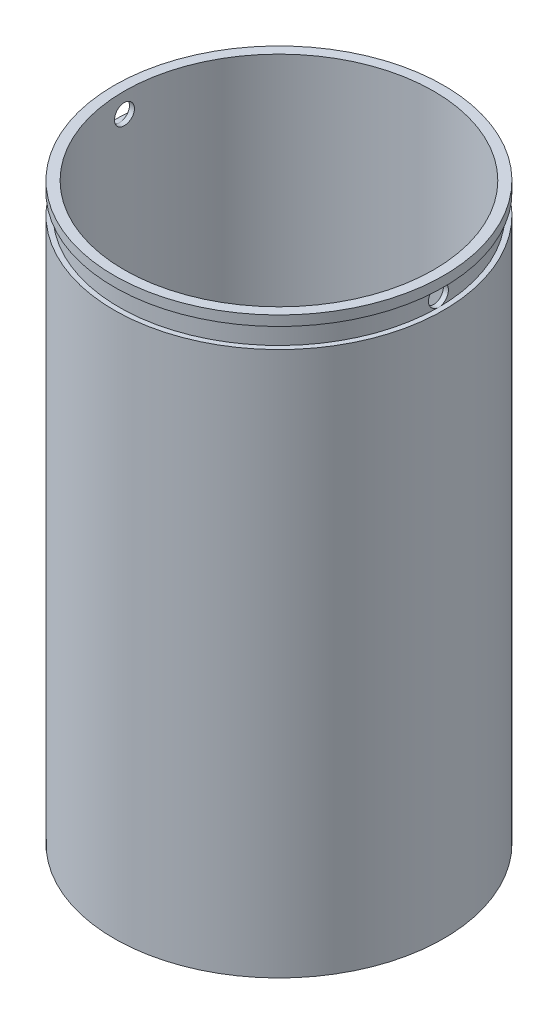
SolidWorks part; units mm, degrees
ref_plane "Plan de face" through (0, 0, 0) normal (0, 0, 1) x (1, 0, 0)
ref_plane "Plan de dessus" through (0, 0, 0) normal (0, 1, 0) x (1, 0, 0)
ref_plane "Plan de droite" through (0, 0, 0) normal (1, 0, 0) x (0, 0, -1)
sketch "Esquisse1" plane through (0, 0, 0) normal (0, 0, 1) x (1, 0, 0)
  line L0 (0, 0) -> (0, 109)
  line L1 (0, 109) -> (1, 109)
  line L2 (1, 109) -> (1, 113)
  line L3 (1, 113) -> (0, 113)
  line L4 (0, 113) -> (0, 115)
  line L5 (0, 115) -> (33, 115)
  line L6 (33, 115) -> (33, 0)
  line L7 (33, 0) -> (0, 0)
  line L8 (33, 183.3357) -> (33, -81.131) construction
  dimension "D1" = 109
  dimension "D2" = 4
  dimension "D3" = 2
  dimension "D4" = 1
  dimension "D5" = 33
revolve "Révolution1" add sketch "Esquisse1" angle 360 about L8
sketch "Esquisse3" plane through (0, 115, 0) normal (0, 1, 0) x (1, 0, 0)
  circle A0 centre (33, 0) radius 31
  circle A3 centre (33, 0) radius 33 construction
  dimension "D1" = 0
  dimension "D2" = 62
extrude "Enlèv. mat.-Extru.2" cut sketch "Esquisse3" against normal blind 113
ref_plane "Plan1" through (65, 0, 0) normal (1, 0, 0) x (0, 0, -1)
sketch "Esquisse4" plane through (65, 0, 0) normal (1, 0, 0) x (0, 0, -1)
  line L0 (-32, 113) -> (32, 113) construction
  line L1 (32, 109) -> (32, 113) construction
  circle A0 centre (0, 111) radius 2
  dimension "D1" = 4
  dimension "D3" = 32
  dimension "D2" = 2
extrude "Enlèv. mat.-Extru.3" cut sketch "Esquisse4" against normal blind 64
sketch "Esquisse6" plane through (0, 0, 0) normal (0, -1, 0) x (1, 0, 0)
  line L0 (33, 0) -> (18.087, 21.298) construction
  line L1 (33, 0) -> (54.298, 14.913) construction
  line L2 (33, 0) -> (33, 11.827) construction
  circle A0 centre (54.298, 14.913) radius 3.5
  circle A1 centre (18.087, 21.298) radius 3.5
  circle A4 centre (11.702, -14.913) radius 3.5
  circle A5 centre (33, 0) radius 33 construction
  circle A6 centre (47.913, -21.298) radius 3.5
  dimension "D2" = 7
  dimension "D1" = 26
  dimension "D3" = 90
  dimension "D4" = 35
extrude "Enlèv. mat.-Extru.5" cut sketch "Esquisse6" against normal blind 10
